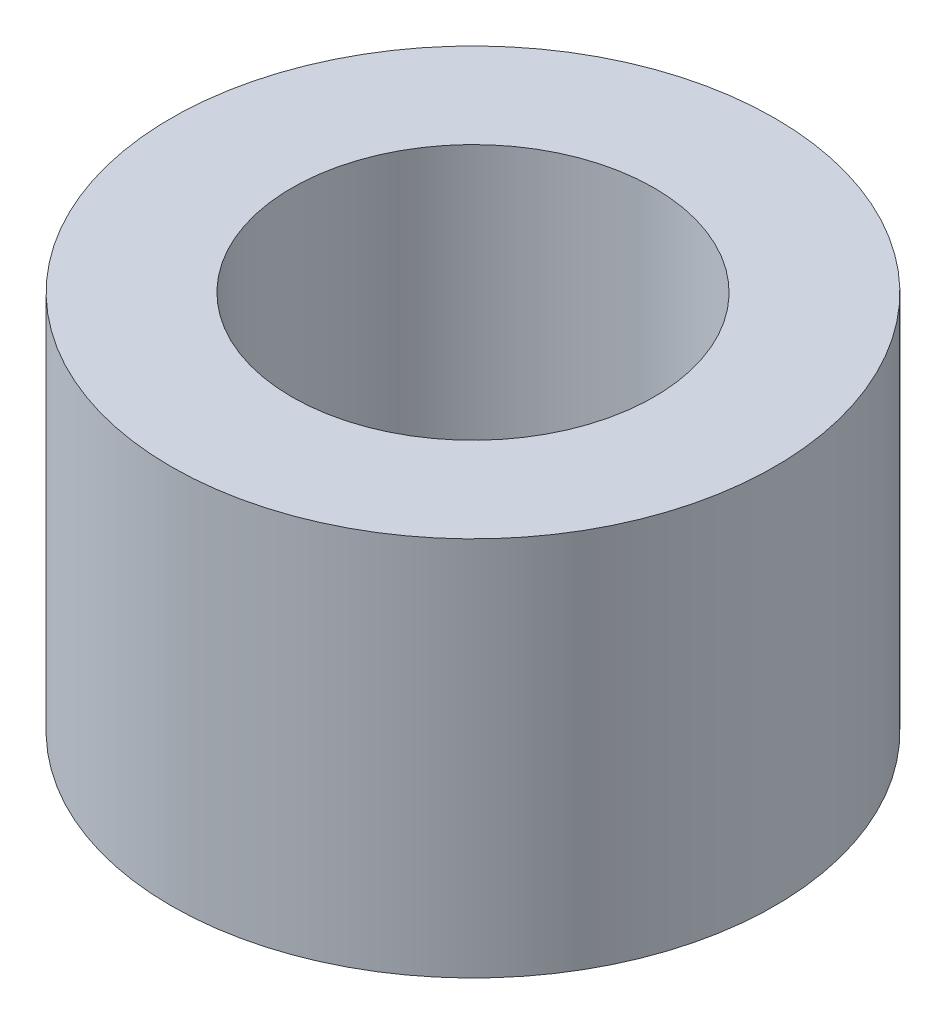
SolidWorks part; units mm, degrees
ref_plane "Alzado" through (0, 0, 0) normal (0, 0, 1) x (1, 0, 0)
ref_plane "Planta" through (0, 0, 0) normal (0, 1, 0) x (1, 0, 0)
ref_plane "Vista lateral" through (0, 0, 0) normal (1, 0, 0) x (0, 0, -1)
sketch "Croquis base" plane through (0, 0, 0) normal (0, 1, 0) x (1, 0, 0)
  circle A0 centre (0, 0) radius 2.5
  dimension "D1" = 5
extrude "Saliente-Extruir1" add sketch "Croquis base" along normal blind 3.15
sketch "Croquis barrenos" plane through (0, 3.15, 0) normal (0, 1, 0) x (1, 0, 0)
  circle A0 centre (0, 0) radius 1.5
  dimension "D1" = 3
extrude "Cortar-Extruir1" cut sketch "Croquis barrenos" against normal through all
